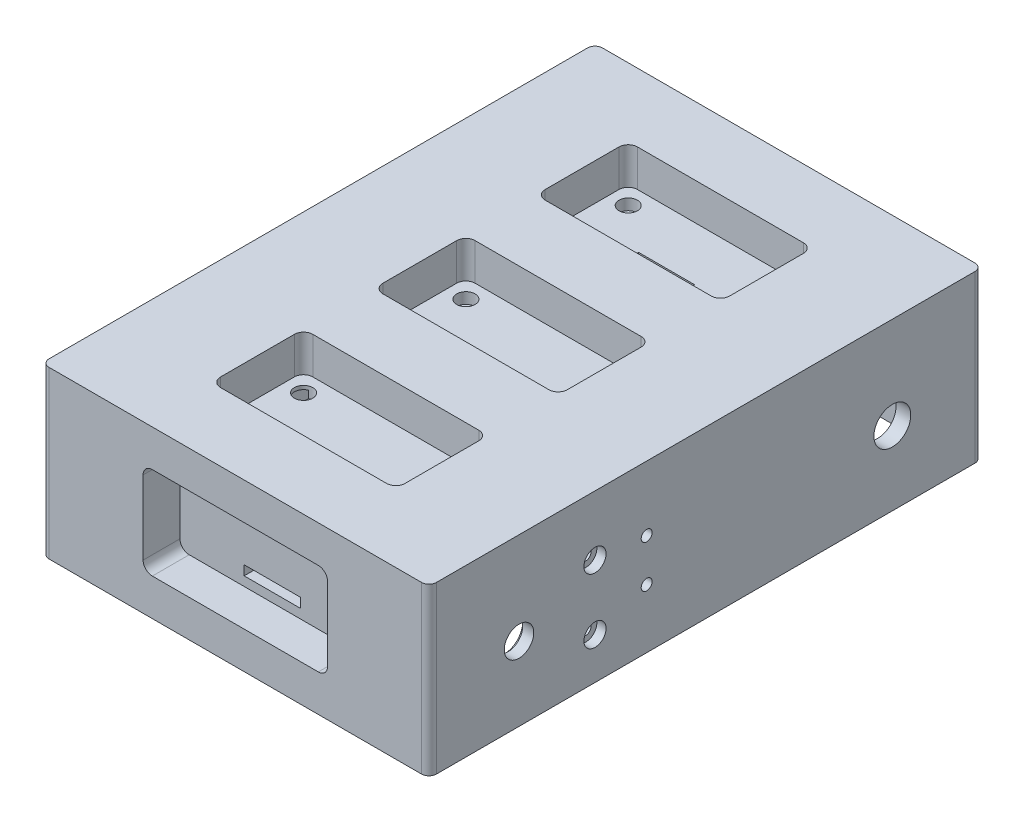
SolidWorks part; units mm, degrees
ref_plane "Спереди" through (0, 0, 0) normal (0, 0, 1) x (1, 0, 0)
ref_plane "Сверху" through (0, 0, 0) normal (0, 1, 0) x (1, 0, 0)
ref_plane "Справа" through (0, 0, 0) normal (1, 0, 0) x (0, 0, -1)
sketch "Эскиз1" plane through (0, 0, 0) normal (0, 1, 0) x (1, 0, 0)
  line L1 (-52.5, -75) -> (52.5, -75)
  line L2 (-52.5, -75) -> (-52.5, 75)
  line L3 (-52.5, 75) -> (52.5, 75)
  line L4 (52.5, -75) -> (52.5, 75)
  line L5 (-52.5, -75) -> (52.5, 75) construction
  line L6 (-52.5, 75) -> (52.5, -75) construction
  point P0 (0, 0)
  dimension "D1" = 105
  dimension "D2" = 150
extrude "Бобышка-Вытянуть1" add sketch "Эскиз1" along normal blind 45
sketch "Эскиз2" plane through (0, 0, 75) normal (0, 0, 1) x (1, 0, 0)
  line L0 (-1050, 22.5) -> (48950, 22.5) construction
  line L1 (-52.5, 45) -> (-52.5, 0) construction
  line L2 (0, -999.2777) -> (0, 49000.7223) construction
  line L4 (-22.5, 10) -> (22.5, 10)
  line L5 (-25, 12.5) -> (-25, 32.5)
  line L6 (-22.5, 35) -> (22.5, 35)
  line L7 (25, 12.5) -> (25, 32.5)
  line L8 (-25, 10) -> (25, 35) construction
  line L9 (-25, 35) -> (25, 10) construction
  arc A0 (-22.5, 35) -> (-25, 32.5) centre (-22.5, 32.5) ccw
  arc A1 (-25, 12.5) -> (-22.5, 10) centre (-22.5, 12.5) ccw
  arc A2 (25, 12.5) -> (22.5, 10) centre (22.5, 12.5) cw
  arc A3 (25, 32.5) -> (22.5, 35) centre (22.5, 32.5) ccw
  point P5 (-52.5, 22.5)
  point P6 (0, 22.5)
  dimension "D3" = 2.5
  dimension "D4" = 2.5
  dimension "D1" = 25
  dimension "D2" = 50
extrude "Вырез-Вытянуть1" cut sketch "Эскиз2" against normal blind 10
sketch "Эскиз4" plane through (0, 45, 0) normal (0, 1, 0) x (1, 0, 0)
  line L0 (0, -1000) -> (0, 49000) construction
  line L1 (-1000, 0) -> (49000, 0) construction
  line L2 (-22.5, 31.5) -> (22.5, 31.5)
  line L3 (-25, 34) -> (-25, 54)
  line L4 (-22.5, 56.5) -> (22.5, 56.5)
  line L5 (-22.5, -12.5) -> (22.5, -12.5)
  line L6 (-25, -10) -> (-25, 10)
  line L7 (-22.5, 12.5) -> (22.5, 12.5)
  line L8 (25, -10) -> (25, 10)
  line L9 (-25, -12.5) -> (25, 12.5) construction
  line L10 (-25, 12.5) -> (25, -12.5) construction
  line L11 (25, 34) -> (25, 54)
  line L12 (-25, 31.5) -> (25, 56.5) construction
  line L13 (-25, 56.5) -> (25, 31.5) construction
  line L14 (-25, -12.5) -> (25, -12.5) [skipped]
  line L15 (-25, -12.5) -> (-25, 12.5) [skipped]
  line L16 (-25, 12.5) -> (25, 12.5) [skipped]
  line L17 (25, -12.5) -> (25, 12.5) [skipped]
  line L18 (-25, -12.5) -> (25, 12.5) construction
  line L19 (-25, 12.5) -> (25, -12.5) construction
  line L20 (-22.5, -56.5) -> (22.5, -56.5)
  line L21 (-25, -54) -> (-25, -34)
  line L22 (-22.5, -31.5) -> (22.5, -31.5)
  line L23 (25, -54) -> (25, -34)
  line L24 (-25, -56.5) -> (25, -31.5) construction
  line L25 (-25, -31.5) -> (25, -56.5) construction
  arc A0 (22.5, -31.5) -> (25, -34) centre (22.5, -34) cw
  arc A1 (25, -54) -> (22.5, -56.5) centre (22.5, -54) cw
  arc A2 (-22.5, -56.5) -> (-25, -54) centre (-22.5, -54) cw
  arc A3 (-25, -34) -> (-22.5, -31.5) centre (-22.5, -34) cw
  arc A4 (-25, 54) -> (-22.5, 56.5) centre (-22.5, 54) cw
  arc A5 (-22.5, 12.5) -> (-25, 10) centre (-22.5, 10) ccw
  arc A6 (25, -10) -> (22.5, -12.5) centre (22.5, -10) cw
  arc A7 (22.5, 56.5) -> (25, 54) centre (22.5, 54) cw
  arc A8 (25, 34) -> (22.5, 31.5) centre (22.5, 34) cw
  arc A9 (-22.5, 31.5) -> (-25, 34) centre (-22.5, 34) cw
  arc A10 (22.5, 12.5) -> (25, 10) centre (22.5, 10) cw
  arc A11 (-22.5, -12.5) -> (-25, -10) centre (-22.5, -10) cw
  point P8 (0, 0)
  point P9 (0, 44)
  point P18 (0, 0)
  point P23 (0, -44)
  dimension "D7" = 2.5
  dimension "D8" = 2.5
  dimension "D1" = 25
  dimension "D2" = 50
  dimension "D5" = 31.5
  dimension "D6" = 31.5
  dimension "D3" = 2
  dimension "D4" = 2
extrude "Вырез-Вытянуть2" cut sketch "Эскиз4" against normal blind 10
mirror "Зеркальное отражение1" about plane through (0, 0, 0) normal (0, 0, 1) of "Вырез-Вытянуть1"
shell "Оболочка1" thickness 4
sketch "Эскиз5" plane through (-52.5, 0, 0) normal (-1, 0, 0) x (0, 0, 1)
  line L0 (30, 28.75) -> (30, 11.25) construction
  line L2 (75, 45) -> (75, 0) construction
  line L4 (-75, 0) -> (75, 0) construction
  line L7 (-1075, 20) -> (48925, 20) construction
  line L8 (-75, 45) -> (-75, 0) construction
  circle A3 centre (30, 28.75) radius 1.45
  circle A4 centre (30, 11.25) radius 1.45
  circle A5 centre (50.6, 20) radius 4
  circle A6 centre (-50.6, 20) radius 5
  dimension "D2" = 17.5
  dimension "D3" = 20
  dimension "D6" = 10
  dimension "D1" = 17.5
  dimension "D5" = 2.9
  dimension "D9" = 45
  dimension "D10" = 20.6
  dimension "D11" = 8
  dimension "D4" = 24.4
extrude "Вырез-Вытянуть3" cut sketch "Эскиз5" against normal blind 15
sketch "Эскиз6" plane through (-52.5, 0, 0) normal (-1, 0, 0) x (0, 0, 1)
  circle A2 centre (30, 28.75) radius 3
  circle A3 centre (30, 11.25) radius 3
  dimension "D1" = 6
extrude "Вырез-Вытянуть4" cut sketch "Эскиз6" against normal blind 2.5
sketch "Эскиз10" plane through (0, 31, 0) normal (0, -1, 0) x (-1, 0, 0)
  line L0 (-22.5, -27.5) -> (22.5, -27.5) construction
  line L1 (21, -27.5) -> (26, -27.5)
  line L2 (21, -27.5) -> (21, -64)
  line L3 (21, -64) -> (26, -64)
  line L4 (26, -27.5) -> (26, -64)
  line L5 (21, -27.5) -> (26, -64) construction
  line L6 (21, -64) -> (26, -27.5) construction
  line L7 (29, -34) -> (29, -54) construction
  point P4 (23.5, -45.75)
  dimension "D1" = 36.5
  dimension "D2" = 3
  dimension "D3" = 5
extrude "Вырез-Вытянуть15" cut sketch "Эскиз10" against normal blind 3 and the other way through all
sketch "Эскиз11" plane through (-48.5, 0, 0) normal (1, 0, 0) x (0, 0, -1)
  circle A1 centre (-50.6, 20) radius 5
  dimension "D1" = 10
extrude "Вырез-Вытянуть16" cut sketch "Эскиз11" against normal blind 1
mirror "Зеркальное отражение2" about plane through (0, 0, 0) normal (1, 0, 0) of "Вырез-Вытянуть16", "Вырез-Вытянуть15", "Вырез-Вытянуть4", "Вырез-Вытянуть3"
sketch "Эскиз12" plane through (0, 6, 0) normal (0, -1, 0) x (-1, 0, 0)
  line L0 (-1014.7864, -63) -> (48985.2136, -63) construction
  line L1 (21, -61) -> (-21, -61) construction
  line L2 (0, -1061) -> (0, 48939) construction
  line L3 (-10, -1061) -> (-10, 48939) construction
  line L4 (10, -1061) -> (10, 48939) construction
  circle A0 centre (-10, -63) radius 1.45
  circle A1 centre (10, -63) radius 1.45
  point P7 (0, -61)
  dimension "D4" = 2.9
  dimension "D1" = 2
  dimension "D2" = 20
  dimension "D3" = 10
extrude "Вырез-Вытянуть17" cut sketch "Эскиз12" against normal blind 14
sketch "Эскиз25" plane through (0, 31, 0) normal (0, -1, 0) x (1, 0, 0)
  line L0 (22.5, 27.5) -> (-22.5, 27.5) construction
  line L1 (-12.5, 27.5) -> (12.5, 27.5)
  line L2 (-12.5, 27.5) -> (-12.5, 16.5)
  line L3 (-12.5, 16.5) -> (12.5, 16.5)
  line L4 (12.5, 27.5) -> (12.5, 16.5)
  line L5 (-12.5, 27.5) -> (12.5, 16.5) construction
  line L6 (-12.5, 16.5) -> (12.5, 27.5) construction
  line L7 (-22.5, 16.5) -> (22.5, 16.5) construction
  point P4 (0, 22)
  point P9 (0, 0)
  dimension "D1" = 25
extrude "Бобышка-Вытянуть2" add sketch "Эскиз25" against normal up to surface (10 mm away) up to face at (0, 41, 44)
sketch "Эскиз13" plane through (0, 31, 0) normal (0, -1, 0) x (-1, 0, 0)
  line L0 (-1008.6674, -25.5) -> (48991.3326, -25.5) construction
  line L2 (0, -1027.5) -> (0, 48972.5) construction
  line L4 (-22.5, -27.5) -> (-12.5, -27.5) construction
  circle A0 centre (-9, -25.5) radius 1.45
  circle A1 centre (9, -25.5) radius 1.45
  dimension "D2" = 18
  dimension "D3" = 2.9
  dimension "D1" = 2
  dimension "D4" = 18
extrude "Вырез-Вытянуть18" cut sketch "Эскиз13" against normal blind 10
sketch "Эскиз14" plane through (0, 31, 0) normal (0, -1, 0) x (-1, 0, 0)
  line L0 (20, -957.2029) -> (20, 49042.7971) construction
  line L1 (29, 54) -> (29, 34) construction
  line L2 (-22.5, 60.5) -> (22.5, 60.5) construction
  line L3 (0, -972.5) -> (0, 49027.5) construction
  line L4 (22.5, 27.5) -> (-22.5, 27.5) construction
  line L5 (-20, -957.2029) -> (-20, 49042.7971) construction
  circle A0 centre (20, 47.5) radius 1.45
  circle A1 centre (20, -7.5) radius 1.45
  circle A2 centre (-20, -7.5) radius 1.45
  circle A3 centre (-20, 47.5) radius 1.45
  point P15 (0, 27.5)
  dimension "D1" = 2.9
  dimension "D3" = 9
  dimension "D2" = 55
  dimension "D4" = 13
extrude "Вырез-Вытянуть19" cut sketch "Эскиз14" against normal blind 3
sketch "Эскиз15" plane through (0, 35, 0) normal (0, 1, 0) x (1, 0, 0)
  line L0 (-1010.1672, -54) -> (48989.8328, -54) construction
  line L1 (0, -1031.5) -> (0, 48968.5) construction
  line L2 (-7.6, -55.3) -> (7.6, -55.3)
  line L3 (-7.6, -55.3) -> (-7.6, -52.7)
  line L4 (-7.6, -52.7) -> (7.6, -52.7)
  line L5 (7.6, -55.3) -> (7.6, -52.7)
  line L6 (-7.6, -55.3) -> (7.6, -52.7) construction
  line L7 (-7.6, -52.7) -> (7.6, -55.3) construction
  line L8 (22.5, -31.5) -> (-22.5, -31.5) construction
  line L9 (-22.5, -56.5) -> (22.5, -56.5) construction
  line L10 (-7.6, -10) -> (7.6, -10)
  line L11 (-7.6, -10) -> (-7.6, -7.4)
  line L12 (-7.6, -7.4) -> (7.6, -7.4)
  line L13 (7.6, -10) -> (7.6, -7.4)
  line L14 (-7.6, -10) -> (7.6, -7.4) construction
  line L15 (-7.6, -7.4) -> (7.6, -10) construction
  line L16 (-7.6, 35.3) -> (7.6, 35.3)
  line L17 (-7.6, 35.3) -> (-7.6, 37.9)
  line L18 (-7.6, 37.9) -> (7.6, 37.9)
  line L19 (7.6, 35.3) -> (7.6, 37.9)
  line L20 (-7.6, 35.3) -> (7.6, 37.9) construction
  line L21 (-7.6, 37.9) -> (7.6, 35.3) construction
  line L22 (-22.5, -12.5) -> (22.5, -12.5) construction
  line L23 (22.5, 12.5) -> (-22.5, 12.5) construction
  line L24 (-7.6, -51.3) -> (7.6, -51.3)
  line L25 (-7.6, -51.3) -> (-7.6, -48.7)
  line L26 (-7.6, -48.7) -> (7.6, -48.7)
  line L27 (7.6, -51.3) -> (7.6, -48.7)
  line L28 (-7.6, -51.3) -> (7.6, -48.7) construction
  line L29 (-7.6, -48.7) -> (7.6, -51.3) construction
  line L30 (-7.6, -6) -> (7.6, -6)
  line L31 (-7.6, -6) -> (-7.6, -3.4)
  line L32 (-7.6, -3.4) -> (7.6, -3.4)
  line L33 (7.6, -6) -> (7.6, -3.4)
  line L34 (-7.6, -6) -> (7.6, -3.4) construction
  line L35 (-7.6, -3.4) -> (7.6, -6) construction
  line L36 (-7.6, 39.3) -> (7.6, 39.3)
  line L37 (-7.6, 39.3) -> (-7.6, 41.9)
  line L38 (-7.6, 41.9) -> (7.6, 41.9)
  line L39 (7.6, 39.3) -> (7.6, 41.9)
  line L40 (-7.6, 39.3) -> (7.6, 41.9) construction
  line L41 (-7.6, 41.9) -> (7.6, 39.3) construction
  circle A0 centre (-20, -36.5) radius 2.5
  circle A1 centre (20, -36.5) radius 2.5
  circle A2 centre (-20, 7.5) radius 2.5
  circle A3 centre (20, 7.5) radius 2.5
  circle A4 centre (-20, 51.5) radius 2.5
  circle A5 centre (20, 51.5) radius 2.5
  point P1 (0, -54)
  point P12 (0, -31.5)
  point P16 (0, -8.7)
  point P21 (0, 36.6)
  point P41 (0, -4.7)
  point P42 (0, -50)
  point P51 (0, 40.6)
  dimension "D6" = 40
  dimension "D8" = 5
  dimension "D1" = 2.6
  dimension "D2" = 15.2
  dimension "D3" = 2.5
  dimension "D4" = 3
  dimension "D5" = 2.5
  dimension "D7" = 40
  dimension "D9" = 5
  dimension "D10" = 3
  dimension "D11" = 5
  dimension "D13" = 4
  dimension "D15" = 4
  dimension "D12" = 2
  dimension "D14" = 3
extrude "Вырез-Вытянуть20" cut sketch "Эскиз15" against normal blind 3
sketch "Эскиз16" plane through (0, 32, 0) normal (0, 1, 0) x (1, 0, 0)
  line L0 (-7.6, -54) -> (7.6, -54) construction
  line L1 (-7.6, -52.7) -> (-7.6, -55.3) construction
  line L2 (7.6, -55.3) -> (7.6, -52.7) construction
  line L3 (0, -1000) -> (0, 49000) construction
  line L4 (-7, -54.9) -> (7, -54.9)
  line L5 (-7, -54.9) -> (-7, -53.1)
  line L6 (-7, -53.1) -> (7, -53.1)
  line L7 (7, -54.9) -> (7, -53.1)
  line L8 (-7, -54.9) -> (7, -53.1) construction
  line L9 (-7, -53.1) -> (7, -54.9) construction
  line L10 (-7, -9.6) -> (7, -9.6)
  line L11 (-7, -9.6) -> (-7, -7.8)
  line L12 (-7, -7.8) -> (7, -7.8)
  line L13 (7, -9.6) -> (7, -7.8)
  line L14 (-7.6, -8.7) -> (7.6, -8.7) construction
  line L15 (-7, -9.6) -> (7, -7.8) construction
  line L16 (-7, -7.8) -> (7, -9.6) construction
  line L17 (-7, 35.7) -> (7, 35.7)
  line L18 (-7, 35.7) -> (-7, 37.5)
  line L19 (-7, 37.5) -> (7, 37.5)
  line L20 (7, 35.7) -> (7, 37.5)
  line L21 (-7.6, 36.6) -> (7.6, 36.6) construction
  line L22 (-7, 35.7) -> (7, 37.5) construction
  line L23 (-7, 37.5) -> (7, 35.7) construction
  line L24 (-7.6, -7.4) -> (-7.6, -10) construction
  line L25 (-7.6, -50) -> (7.6, -50) construction
  line L26 (-7, -50.9) -> (7, -50.9)
  line L27 (-7, -50.9) -> (-7, -49.1)
  line L28 (-7, -49.1) -> (7, -49.1)
  line L29 (7, -50.9) -> (7, -49.1)
  line L30 (-7, -50.9) -> (7, -49.1) construction
  line L31 (-7, -49.1) -> (7, -50.9) construction
  line L32 (-7.6, -48.7) -> (-7.6, -51.3) construction
  line L33 (7.6, -51.3) -> (7.6, -48.7) construction
  line L34 (-7.6, -4.7) -> (7.6, -4.7) construction
  line L35 (-7.6, -3.4) -> (-7.6, -6) construction
  line L36 (7.6, -6) -> (7.6, -3.4) construction
  line L37 (-7.6, -10) -> (7.6, -10) construction
  line L38 (-7, -5.6) -> (7, -5.6)
  line L39 (-7, -5.6) -> (-7, -3.8)
  line L40 (-7, -3.8) -> (7, -3.8)
  line L41 (7, -5.6) -> (7, -3.8)
  line L42 (-7, -5.6) -> (7, -3.8) construction
  line L43 (-7, -3.8) -> (7, -5.6) construction
  line L44 (7.6, -10) -> (7.6, -7.4) construction
  line L45 (-7.6, 37.9) -> (-7.6, 35.3) construction
  line L46 (7.6, 35.3) -> (7.6, 37.9) construction
  line L47 (-7.6, 35.3) -> (7.6, 35.3) construction
  line L48 (-7.6, 40.6) -> (7.6, 40.6) construction
  line L49 (-7.6, 41.9) -> (-7.6, 39.3) construction
  line L50 (7.6, 39.3) -> (7.6, 41.9) construction
  line L52 (-7, 39.7) -> (7, 39.7)
  line L53 (-7, 39.7) -> (-7, 41.5)
  line L54 (-7, 41.5) -> (7, 41.5)
  line L55 (7, 39.7) -> (7, 41.5)
  line L56 (-7, 39.7) -> (7, 41.5) construction
  line L57 (-7, 41.5) -> (7, 39.7) construction
  point P6 (0, -54)
  point P12 (0, -50)
  point P17 (0, -8.7)
  point P24 (0, 36.6)
  point P41 (0, -4.7)
  point P54 (0, 40.6)
  point P67 (-7, 39.1942)
  point P68 (0, 40.6)
  dimension "D1" = 1.8
  dimension "D2" = 14
  dimension "D4" = 0.4
  dimension "D3" = 0.4
extrude "Вырез-Вытянуть21" cut sketch "Эскиз16" against normal blind 3
sketch "Эскиз17" plane through (0, 0, 65) normal (0, 0, 1) x (1, 0, 0)
  line L0 (-7.6, 12.5) -> (7.6, 12.5)
  line L1 (-7.6, 12.5) -> (-7.6, 15.1)
  line L2 (-7.6, 15.1) -> (7.6, 15.1)
  line L3 (7.6, 12.5) -> (7.6, 15.1)
  line L4 (-7.6, 12.5) -> (7.6, 15.1) construction
  line L5 (-7.6, 15.1) -> (7.6, 12.5) construction
  line L8 (-22.5, 10) -> (22.5, 10) construction
  line L9 (0, -965) -> (0, 49035) construction
  line L10 (22.5, 35) -> (-22.5, 35) construction
  circle A0 centre (-20, 30) radius 2.5
  circle A1 centre (20, 30) radius 2.5
  point P0 (0, 13.8)
  point P20 (0, 35)
  dimension "D5" = 5
  dimension "D1" = 2.6
  dimension "D2" = 15.2
  dimension "D3" = 40
  dimension "D4" = 40
  dimension "D6" = 2.5
  dimension "D7" = 5
extrude "Вырез-Вытянуть22" cut sketch "Эскиз17" against normal blind 3
sketch "Эскиз18" plane through (0, 0, 62) normal (0, 0, 1) x (1, 0, 0)
  line L0 (-7.6, 13.8) -> (7.6, 13.8) construction
  line L1 (-7.6, 15.1) -> (-7.6, 12.5) construction
  line L2 (7.6, 12.5) -> (7.6, 15.1) construction
  line L4 (-7, 12.9) -> (7, 12.9)
  line L5 (-7, 12.9) -> (-7, 14.7)
  line L6 (-7, 14.7) -> (7, 14.7)
  line L7 (7, 12.9) -> (7, 14.7)
  line L8 (-7, 12.9) -> (7, 14.7) construction
  line L9 (-7, 14.7) -> (7, 12.9) construction
  point P6 (0, 13.8)
  dimension "D1" = 1.8
  dimension "D2" = 14
extrude "Вырез-Вытянуть23" cut sketch "Эскиз18" against normal blind 3
sketch "Эскиз19" plane through (0, 0, -65) normal (0, 0, -1) x (1, 0, 0)
  line L0 (-7.6, -32.5) -> (7.6, -32.5)
  line L1 (-7.6, -32.5) -> (-7.6, -29.9)
  line L2 (-7.6, -29.9) -> (7.6, -29.9)
  line L3 (7.6, -32.5) -> (7.6, -29.9)
  line L4 (-7.6, -32.5) -> (7.6, -29.9) construction
  line L5 (-7.6, -29.9) -> (7.6, -32.5) construction
  line L6 (0, -1010) -> (0, 48990) construction
  line L7 (-22.5, -10) -> (22.5, -10) construction
  line L10 (22.5, -35) -> (-22.5, -35) construction
  circle A0 centre (-20, -15) radius 2.5
  circle A1 centre (20, -15) radius 2.5
  point P0 (0, -31.2)
  point P14 (0, -10)
  dimension "D5" = 5
  dimension "D7" = 2.5
  dimension "D1" = 2.6
  dimension "D2" = 15.2
  dimension "D3" = 40
  dimension "D4" = 40
  dimension "D6" = 5
extrude "Вырез-Вытянуть24" cut sketch "Эскиз19" against normal blind 3
sketch "Эскиз20" plane through (0, 0, -62) normal (0, 0, -1) x (1, 0, 0)
  line L0 (-1007.6, -31.2) -> (48992.4, -31.2) construction
  line L1 (-7.6, -29.9) -> (-7.6, -32.5) construction
  line L3 (-7, -32.1) -> (7, -32.1)
  line L4 (-7, -32.1) -> (-7, -30.3)
  line L5 (-7, -30.3) -> (7, -30.3)
  line L6 (7, -32.1) -> (7, -30.3)
  line L7 (-7, -32.1) -> (7, -30.3) construction
  line L8 (-7, -30.3) -> (7, -32.1) construction
  line L10 (0, -1029.9) -> (0, 48970.1) construction
  line L11 (7.6, -29.9) -> (-7.6, -29.9) construction
  point P1 (0, -31.2)
  point P5 (-7.6, -31.2)
  point P18 (0, -29.9)
  dimension "D1" = 1.8
  dimension "D2" = 14
extrude "Вырез-Вытянуть25" cut sketch "Эскиз20" against normal blind 8
sketch "Эскиз21" plane through (0, 0, -75) normal (0, 0, -1) x (1, 0, 0)
  line L0 (-975, -22.5) -> (49025, -22.5) construction
  line L1 (37.75, -29.75) -> (47.25, -29.75)
  line L2 (37.75, -29.75) -> (37.75, -15.25)
  line L3 (37.75, -15.25) -> (47.25, -15.25)
  line L4 (47.25, -29.75) -> (47.25, -15.25)
  line L5 (37.75, -29.75) -> (47.25, -15.25) construction
  line L6 (37.75, -15.25) -> (47.25, -29.75) construction
  line L7 (25, -12.5) -> (25, -32.5) construction
  line L8 (42.5, -1022.5) -> (42.5, 48977.5) construction
  line L9 (52.5, -45) -> (52.5, 0) construction
  point P0 (42.5, -22.5)
  point P10 (25, -22.5)
  dimension "D1" = 9.5
  dimension "D2" = 14.5
  dimension "D3" = 10
extrude "Вырез-Вытянуть26" cut sketch "Эскиз21" against normal blind 4
sketch "Эскиз22" plane through (0, 0, 0) normal (0, -1, 0) x (-1, 0, 0)
  line L0 (-50.5, -925) -> (-50.5, 49075) construction
  line L2 (-52.5, -75) -> (-52.5, 75) construction
  line L3 (-1046.2998, 73) -> (48953.7002, 73) construction
  line L4 (-52.5, 75) -> (52.5, 75) construction
  line L5 (50.5, -925) -> (50.5, 49075) construction
  line L6 (52.5, 75) -> (52.5, -75) construction
  line L7 (-1052.5, -73) -> (48947.5, -73) construction
  line L8 (52.5, -75) -> (-52.5, -75) construction
  line L9 (0, -925) -> (0, 49075) construction
  line L10 (-1052.5, 0) -> (48947.5, 0) construction
  circle A0 centre (-50.5, -73) radius 1.425
  circle A1 centre (-50.5, 73) radius 1.425
  circle A2 centre (50.5, 73) radius 1.425
  circle A3 centre (50.5, -73) radius 1.425
  circle A4 centre (0, 73) radius 1.425
  circle A5 centre (0, -73) radius 1.425
  circle A6 centre (-50.5, 0) radius 1.425
  circle A7 centre (50.5, 0) radius 1.425
  point P27 (0, 75)
  point P34 (-52.5, 0)
  dimension "D5" = 2.85
  dimension "D1" = 2
  dimension "D2" = 2
  dimension "D3" = 2
  dimension "D4" = 2
extrude "Вырез-Вытянуть27" cut sketch "Эскиз22" against normal blind 9
sketch "Эскиз24" plane through (-52.5, 0, 0) normal (-1, 0, 0) x (0, 0, 1)
  line L0 (0, -1000) -> (0, 49000) construction
  line L1 (16, -988.2808) -> (16, 49011.7192) construction
  line L2 (-75, 0) -> (75, 0) construction
  circle A0 centre (16, 16) radius 1.475
  circle A1 centre (16, 27.5) radius 1.475
  dimension "D4" = 2.95
  dimension "D1" = 11.5
  dimension "D2" = 16
  dimension "D3" = 16
extrude "Вырез-Вытянуть28" cut sketch "Эскиз24" against normal through all
fillet "Скругление1" radius 2 4 edges at (52.5, 22.5, -75) (-52.5, 22.5, -75) (52.5, 22.5, 75) (-52.5, 22.5, 75)
